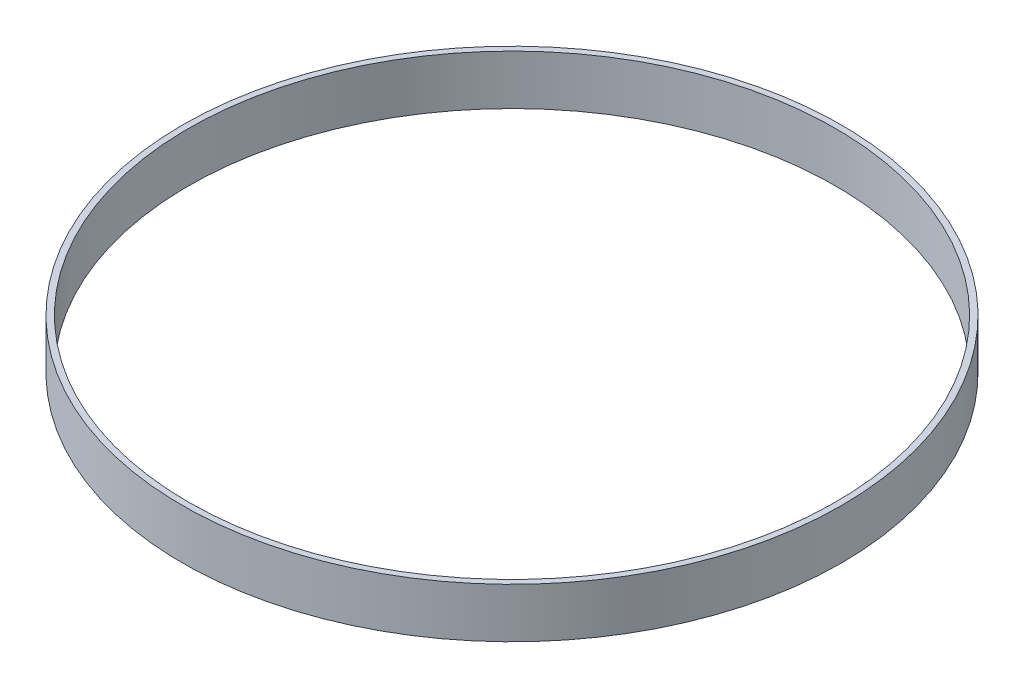
SolidWorks part; units mm, degrees
ref_plane "Front Plane" through (0, 0, 0) normal (0, 0, 1) x (1, 0, 0)
ref_plane "Top Plane" through (0, 0, 0) normal (0, 1, 0) x (1, 0, 0)
ref_plane "Right Plane" through (0, 0, 0) normal (1, 0, 0) x (0, 0, -1)
sketch "Sketch1" plane through (0, 0, 0) normal (0, 1, 0) x (1, 0, 0)
  circle A0 centre (0, 0) radius 65
  dimension "D1" = 130
extrude "Extrude-Thin1" add sketch "Sketch1" along normal blind 10 thin contours A0
